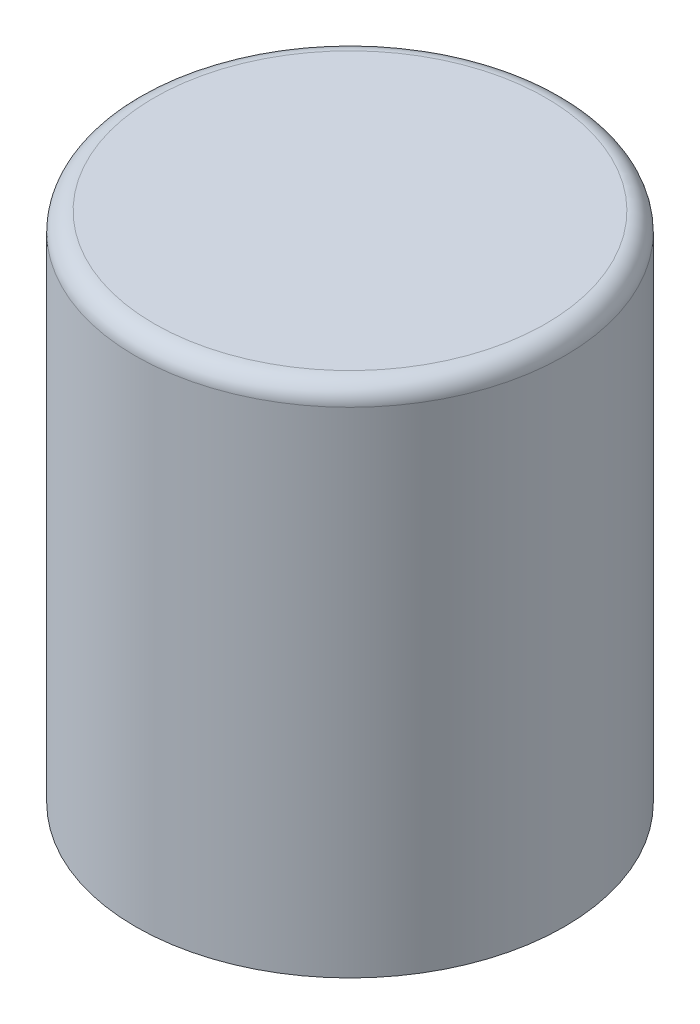
SolidWorks part; units mm, degrees
ref_plane "前视基准面" through (0, 0, 0) normal (0, 0, 1) x (1, 0, 0)
ref_plane "上视基准面" through (0, 0, 0) normal (0, 1, 0) x (1, 0, 0)
ref_plane "右视基准面" through (0, 0, 0) normal (1, 0, 0) x (0, 0, -1)
sketch "草图1" plane through (0, 0, 0) normal (0, 1, 0) x (1, 0, 0)
  circle A0 centre (0, 0) radius 2.3
  dimension "D1" = 4.6
extrude "凸台-拉伸1" add sketch "草图1" along normal blind 5.5
fillet "圆角1" radius 0.2 1 edges at (0, 5.5, 2.3)
sketch "草图2" plane through (0, 0, 0) normal (0, -1, 0) x (1, 0, 0)
  line L0 (-3.4011, 0) -> (3.0245, 0) construction
  line L1 (-1.2, 1.2) -> (1.2, 1.2)
  line L2 (-1.2, 1.2) -> (-1.2, -1.2)
  line L3 (-1.2, -1.2) -> (1.2, -1.2)
  line L4 (1.2, 1.2) -> (1.2, -1.2)
  line L5 (0, 2.4595) -> (0, -2.6478) construction
  dimension "D1" = 2.4
  dimension "D2" = 2.4
extrude "切除-拉伸1" cut sketch "草图2" against normal blind 3.1
